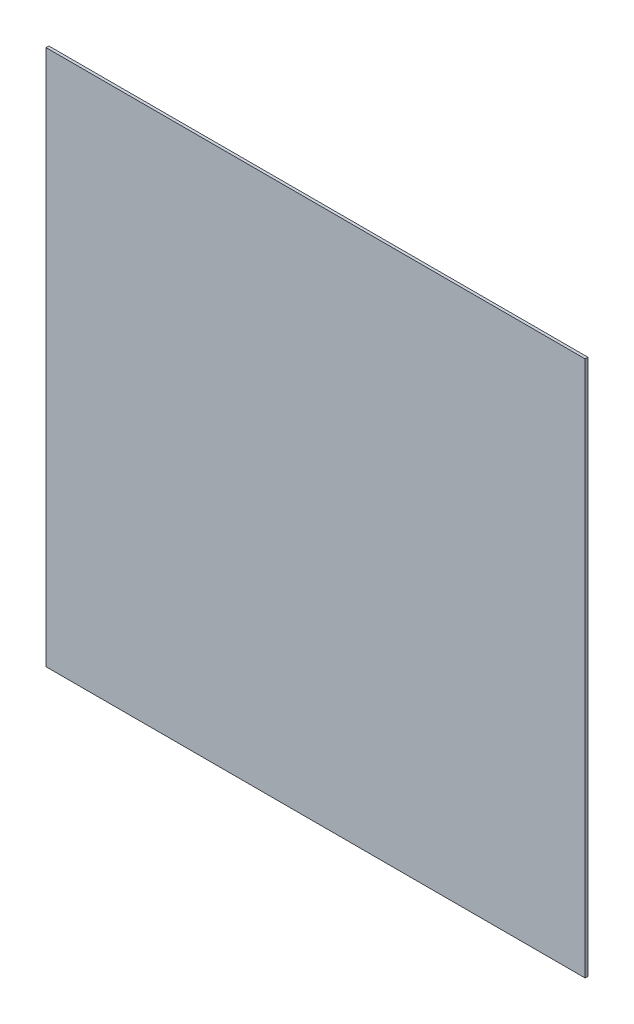
SolidWorks part; units mm, degrees
ref_plane "Front Plane" through (0, 0, 0) normal (0, 0, 1) x (1, 0, 0)
ref_plane "Top Plane" through (0, 0, 0) normal (0, 1, 0) x (1, 0, 0)
ref_plane "Right Plane" through (0, 0, 0) normal (1, 0, 0) x (0, 0, -1)
sketch "Sketch1" plane through (0, 0, 0) normal (0, 0, 1) x (1, 0, 0)
  line L1 (-304.8, -303.2125) -> (304.8, -303.2125)
  line L2 (-304.8, -303.2125) -> (-304.8, 303.2125)
  line L3 (-304.8, 303.2125) -> (304.8, 303.2125)
  line L4 (304.8, -303.2125) -> (304.8, 303.2125)
  line L5 (-304.8, -303.2125) -> (304.8, 303.2125) construction
  line L6 (-304.8, 303.2125) -> (304.8, -303.2125) construction
  point P0 (0, 0)
  dimension "D1" = 609.6
  dimension "D2" = 606.425
extrude "Boss-Extrude1" add sketch "Sketch1" along normal blind 3.175
